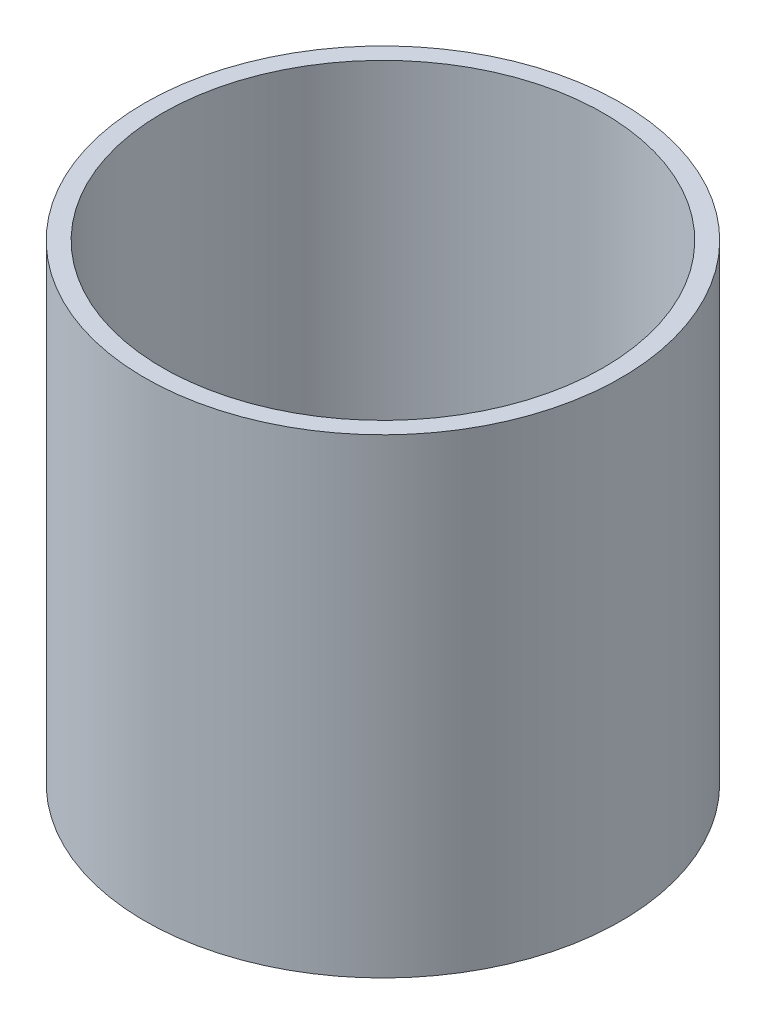
SolidWorks part; units mm, degrees
ref_plane "Front Plane" through (0, 0, 0) normal (0, 0, 1) x (1, 0, 0)
ref_plane "Top Plane" through (0, 0, 0) normal (0, 1, 0) x (1, 0, 0)
ref_plane "Right Plane" through (0, 0, 0) normal (1, 0, 0) x (0, 0, -1)
sketch "Sketch1" plane through (0, 0, 0) normal (0, 0, 1) x (1, 0, 0)
  line L0 (0, 0) -> (-40.5, 0)
  line L1 (-40.5, 0) -> (-40.5, 80)
  line L3 (-37.5, 80) -> (-37.5, 15.5)
  line L4 (-27.5, 5.5) -> (0, 5.5)
  line L5 (0, 5.5) -> (0, 0)
  line L11 (-40.5, 80) -> (-37.5, 80)
  arc A0 (-37.5, 15.5) -> (-27.5, 5.5) centre (-27.5, 15.5) ccw
  point P9 (-37.5, 5.5)
  dimension "D3" = 10
  dimension "D1" = 37.5
  dimension "D2" = 80
  dimension "D4" = 3
  dimension "D5" = 5.5
revolve "Revolve1" add sketch "Sketch1" angle 360 about L5
sketch "Sketch2" plane through (0, 0, 0) normal (0, -1, 0) x (1, 0, 0)
  circle A0 centre (0, 0) radius 12.7 construction
  circle A1 centre (0, 12.7) radius 2.3
  point P3 (0, 12.7)
  point P7 (8.9803, 8.9803)
  point P8 (12.7, 0)
  point P9 (8.9803, -8.9803)
  point P10 (0, -12.7)
  point P11 (-8.9803, -8.9803)
  point P12 (-12.7, 0)
  point P13 (-8.9803, 8.9803)
  point P14 (0, 0)
  dimension "D1" = 25.4
  dimension "D3" = 4.6
  dimension "D2" = 8
extrude "Cut-Extrude1" cut sketch "Sketch2" against normal up to next (5.5 mm away) draft 4.35 contours A1
pattern_circular "CirPattern1" count 4 over 360 about axis through (0, 0, 0) along (0, 1, 0) of "Cut-Extrude1"
fillet "Fillet1" [suppressed] radius 0.3969
chamfer "Chamfer1" [suppressed] distance 0.3969 angle 45
ref_plane "Plane1" [suppressed] through (43.18, 0, 0) normal (1, 0, 0) x (0, 0, -1)
sketch "Sketch3" [suppressed] plane through (43.18, 0, 0) normal (1, 0, 0) x (0, 0, -1)
  line L0 (-43.18, 0) -> (43.18, 0) construction
  line L1 (43.18, 152.4) -> (-43.18, 152.4) construction
  line L2 (-43.18, 0) -> (43.18, 0) construction
  line L3 (43.18, 152.4) -> (-43.18, 152.4) construction
  line L4 (0, 0) -> (0, 152.4) construction
  circle A0 centre (0, 36.8078) radius 1
  circle A1 centre (0, 56.4155) radius 2.5
  circle A2 centre (0, 86.1841) radius 3.5
  circle A3 centre (0, 120.2598) radius 5
  dimension "D1" = 2
  dimension "D2" = 5
  dimension "D3" = 7
  dimension "D4" = 10
extrude "Cut-Extrude2" [suppressed] cut sketch "Sketch3" against normal up to next
